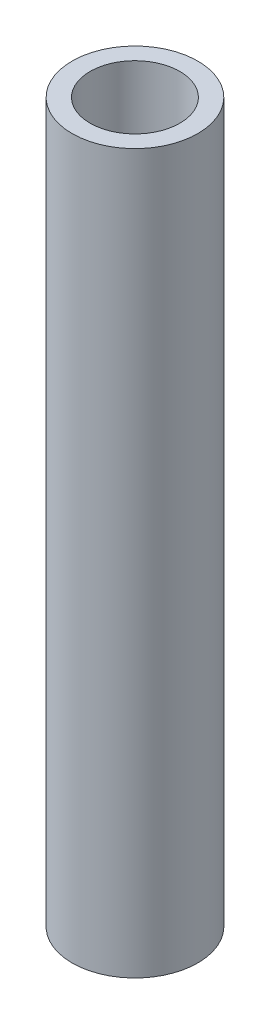
SolidWorks part; units mm, degrees
ref_plane "Front Plane" through (0, 0, 0) normal (0, 0, 1) x (1, 0, 0)
ref_plane "Top Plane" through (0, 0, 0) normal (0, 1, 0) x (1, 0, 0)
ref_plane "Right Plane" through (0, 0, 0) normal (1, 0, 0) x (0, 0, -1)
sketch "Sketch1" plane through (0, 0, 0) normal (0, 1, 0) x (1, 0, 0)
  circle A0 centre (0, 0) radius 7
extrude "Boss-Extrude1" add sketch "Sketch1" along normal blind 80
sketch "Sketch2" plane through (0, 80, 0) normal (0, 1, 0) x (1, 0, 0)
  circle A0 centre (0, 0) radius 5
extrude "Cut-Extrude1" cut sketch "Sketch2" against normal blind 20
